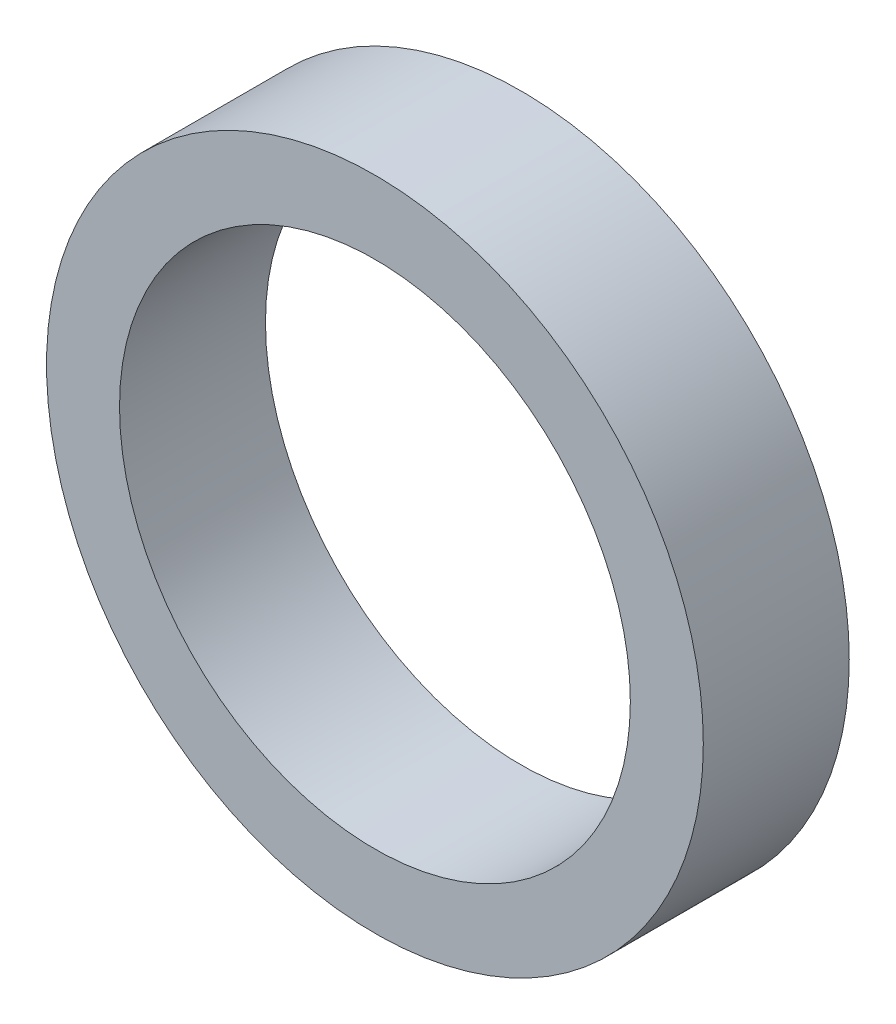
SolidWorks part; units mm, degrees
ref_plane "Plan de face" through (0, 0, 0) normal (0, 0, 1) x (1, 0, 0)
ref_plane "Plan de dessus" through (0, 0, 0) normal (0, 1, 0) x (1, 0, 0)
ref_plane "Plan de droite" through (0, 0, 0) normal (1, 0, 0) x (0, 0, -1)
sketch "Esquisse1" plane through (0, 0, 0) normal (0, 0, 1) x (1, 0, 0)
  circle A0 centre (0, 0) radius 17.5
  circle A1 centre (0, 0) radius 22.5
  dimension "D1" = 35
  dimension "D2" = 45
extrude "Boss.-Extru.1" add sketch "Esquisse1" along normal blind 10
